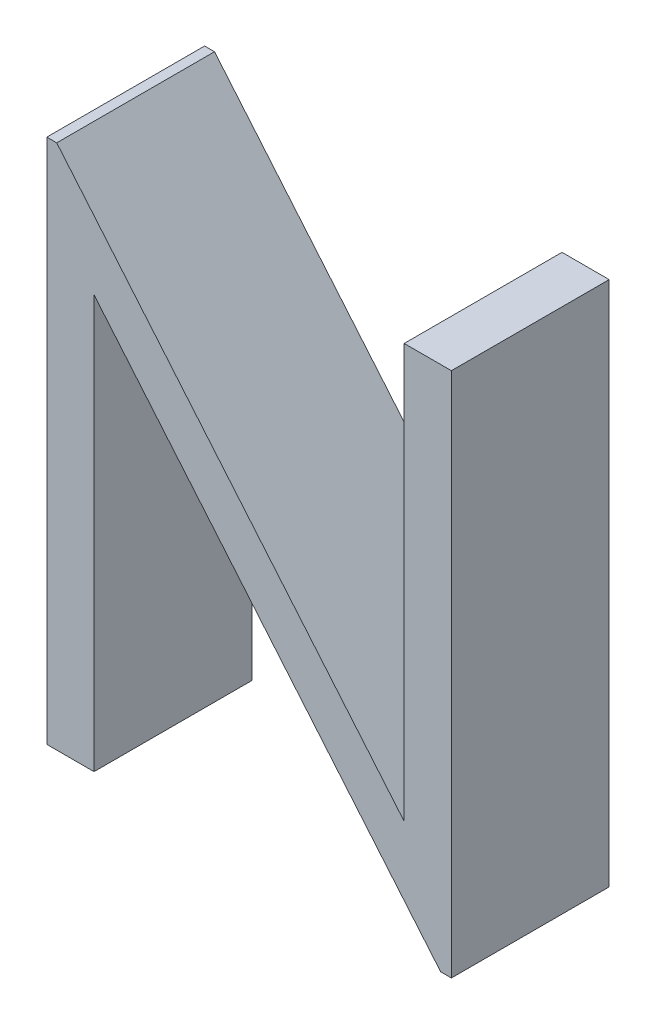
SolidWorks part; units mm, degrees
ref_plane "Plan de face" through (0, 0, 0) normal (0, 0, 1) x (1, 0, 0)
ref_plane "Plan de dessus" through (0, 0, 0) normal (0, 1, 0) x (1, 0, 0)
ref_plane "Plan de droite" through (0, 0, 0) normal (1, 0, 0) x (0, 0, -1)
sketch "Esquisse1" plane through (0, 0, 0) normal (0, 0, 1) x (1, 0, 0)
  text T0 "N" font "Century Gothic" height 5
extrude "Boss.-Extru.1" add sketch "Esquisse1" along normal blind 1.5
